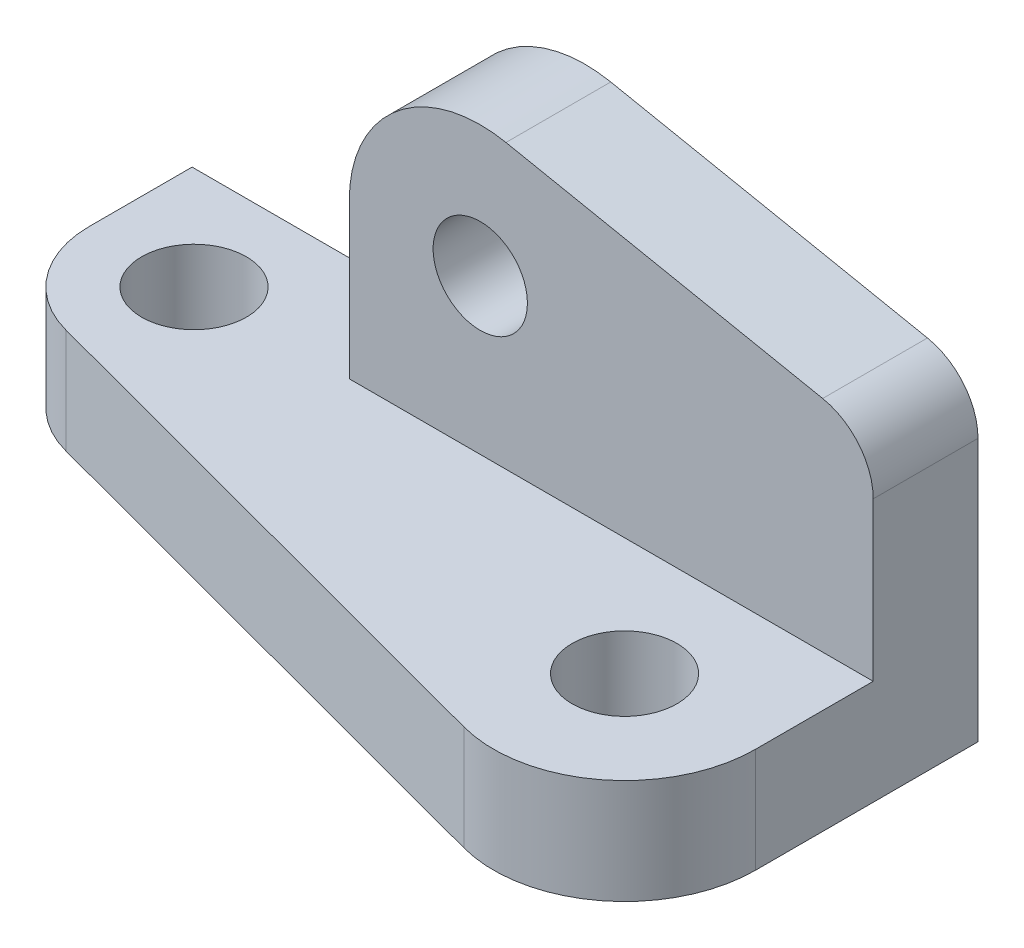
SolidWorks part; units mm, degrees
ref_plane "Front Plane" through (0, 0, 0) normal (0, 0, 1) x (1, 0, 0)
ref_plane "Top Plane" through (0, 0, 0) normal (0, 1, 0) x (1, 0, 0)
ref_plane "Right Plane" through (0, 0, 0) normal (1, 0, 0) x (0, 0, -1)
sketch "Sketch1" plane through (0, 0, 0) normal (0, 1, 0) x (1, 0, 0)
  line L0 (0, 0) -> (150, 0)
  line L1 (150, 0) -> (150, -75)
  line L2 (150, -75) -> (0, -35)
  line L3 (0, -35) -> (0, 0)
  dimension "D1" = 150
  dimension "D2" = 75
  dimension "D3" = 35
extrude "Boss-Extrude1" add sketch "Sketch1" along normal blind 20
sketch "Sketch2" plane through (0, 0, 0) normal (0, 0, -1) x (-1, 0, 0)
  line L0 (-150, 0) -> (-150, 60)
  line L1 (-150, 60) -> (-50, 80)
  line L2 (-50, 80) -> (-50, 0)
  line L3 (-150, 0) -> (0, 0) construction
  line L4 (-50, 0) -> (-150, 0)
  dimension "D1" = 80
  dimension "D2" = 60
  dimension "D3" = 100
extrude "Boss-Extrude2" add sketch "Sketch2" against normal blind 20
fillet "Fillet1" radius 20 1 edges at (0, 10, 35)
fillet "Fillet2" radius 25 2 edges at (50, 80, 10) (150, 10, 75)
fillet "Fillet3" radius 12 1 edges at (150, 60, 10)
hole_wizard "Ø18.0 (18) Diameter Hole1" positions "Sketch7" profile "Sketch8" hole size "Ø18.0" standard "ANSI Metric" end condition through all
sketch "Sketch7" plane through (0, 0, 20) normal (0, 0, 1) x (1, 0, 0)
  point P0 (75, 49.5049)
sketch "Sketch8" plane through (75, 49.5049, 20) normal (1, 0, 0) x (0, -1, 0)
  line L0 (0, 0) -> (0, 20)
  line L1 (0, 20) -> (9, 20)
  line L2 (9, 20) -> (9, 0)
  line L5 (9, 0) -> (0, 0)
  line L11 (0, -6.35) -> (0, 107.95) construction
  dimension "Thru Hole Dia." = 18
  dimension "Thru Hole Depth" = 20
hole_wizard "Ø20.0 (20) Diameter Hole1" positions "Sketch9" profile "Sketch10" hole size "Ø20.0" standard "ANSI Metric" end condition through all
sketch "Sketch9" plane through (0, 20, 0) normal (0, 1, 0) x (1, 0, 0)
  point P0 (20, -19.6344)
  point P3 (125, -42.4597)
sketch "Sketch10" plane through (20, 20, 19.6344) normal (1, 0, 0) x (0, 0, 1)
  line L0 (0, 0) -> (0, 20)
  line L1 (0, 20) -> (10, 20)
  line L2 (10, 20) -> (10, 0)
  line L5 (10, 0) -> (0, 0)
  line L11 (0, -6.35) -> (0, 107.95) construction
  dimension "Thru Hole Dia." = 20
  dimension "Thru Hole Depth" = 20
